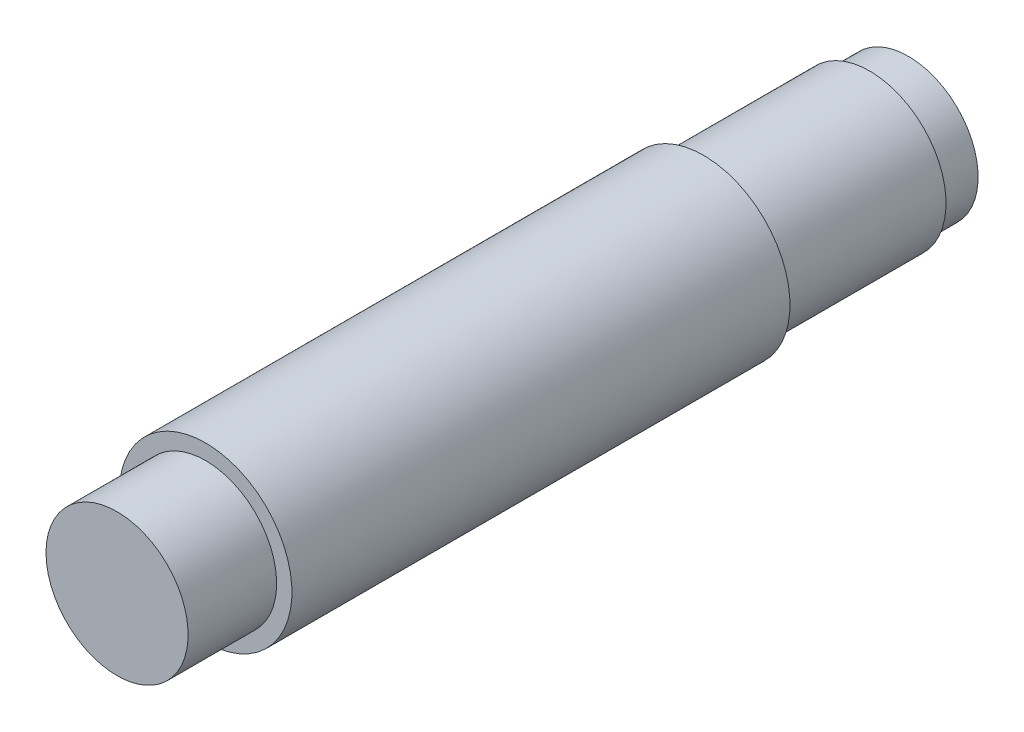
SolidWorks part; units mm, degrees
ref_plane "Front Plane" through (0, 0, 0) normal (0, 0, 1) x (1, 0, 0)
ref_plane "Top Plane" through (0, 0, 0) normal (0, 1, 0) x (1, 0, 0)
ref_plane "Right Plane" through (0, 0, 0) normal (1, 0, 0) x (0, 0, -1)
sketch "Sketch2" plane through (0, 0, 0) normal (0, 1, 0) x (1, 0, 0)
  line L0 (0, 11.1838) -> (0, -24.5662)
  line L1 (0, -24.5662) -> (3.21, -24.5662)
  line L2 (3.21, -24.5662) -> (3.21, -20.5662)
  line L3 (3.21, -20.5662) -> (3.9, -20.5662)
  line L4 (3.9, -20.5662) -> (3.9, 1.9338)
  line L5 (3.9, 1.9338) -> (3.45, 1.9338)
  line L6 (3.45, 1.9338) -> (3.45, 9.4338)
  line L7 (3.45, 9.4338) -> (3.15, 9.4338)
  line L8 (3.15, 9.4338) -> (3.15, 11.1838)
  line L9 (3.15, 11.1838) -> (0, 11.1838)
  line L10 (0, 14.019) -> (0, -34.9916) construction
  dimension "D1" = 22.5
  dimension "D2" = 4
  dimension "D3" = 7.5
  dimension "D4" = 1.75
  dimension "D5" = 3.21
  dimension "D6" = 3.9
  dimension "D7" = 3.45
  dimension "D8" = 3.15
revolve "Revolve2" add sketch "Sketch2" angle 360 about L10
